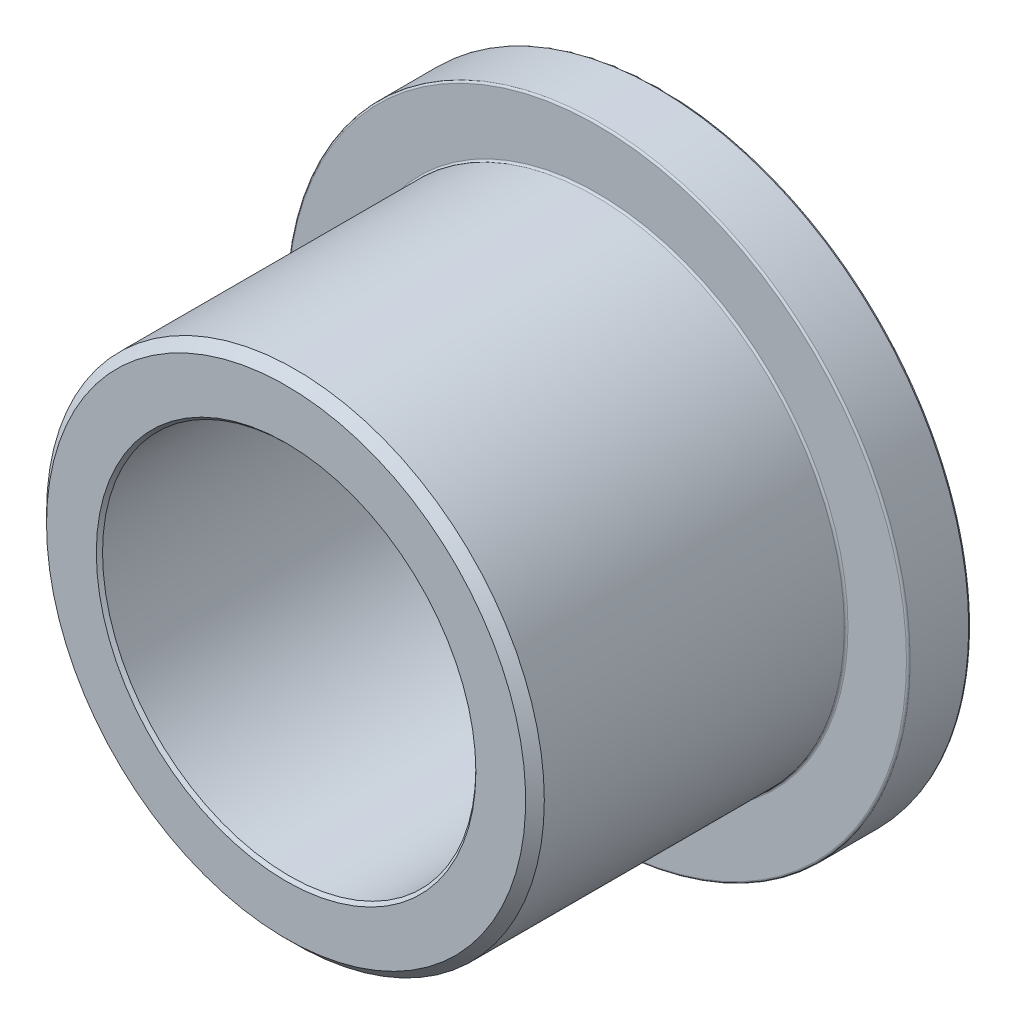
SolidWorks part; units mm, degrees
ref_plane "Front Plane" through (0, 0, 0) normal (0, 0, 1) x (1, 0, 0)
ref_plane "Top Plane" through (0, 0, 0) normal (0, 1, 0) x (1, 0, 0)
ref_plane "Right Plane" through (0, 0, 0) normal (1, 0, 0) x (0, 0, -1)
sketch "Sketch1" plane through (0, 0, 0) normal (0, 0, 1) x (1, 0, 0)
  circle A0 centre (0, 0) radius 4.7625 construction
  circle A1 centre (0, 0) radius 6.35 construction
  circle A2 centre (0, 0) radius 7.9375 construction
  point P5 (0, 7.9375)
  dimension "ID" = 9.525
  dimension "OD" = 12.7
  dimension "Flange OD" = 15.875
sketch "Sketch2" plane through (0, 0, 0) normal (1, 0, 0) x (0, 0, -1)
  line L0 (-4.7625, 0) -> (4.7625, 0) construction
  line L1 (-4.7625, 6.35) -> (-4.7625, -6.35) construction
  line L2 (0, 6.35) -> (0, -6.35) construction
  line L3 (4.7625, 7.9375) -> (4.7625, -7.9375) construction
  line L4 (0, 7.9375) -> (0, -7.9375) construction
  line L5 (4.7625, -7.9375) -> (3.175, -7.9375) construction
  dimension "Length" = 9.525
  dimension "Flange Thickness" = 1.5875
sketch "Sketch3" plane through (0, 0, 0) normal (1, 0, 0) x (0, 0, -1)
  line L0 (4.7625, -7.9375) -> (3.175, -7.9375)
  line L1 (3.175, -7.9375) -> (3.175, -6.35)
  line L2 (3.175, -6.35) -> (-4.7625, -6.35)
  line L3 (-4.7625, -6.35) -> (-4.7625, -4.7625)
  line L4 (-4.7625, 6.35) -> (-4.7625, -6.35) construction
  line L5 (-4.7625, -4.7625) -> (4.7625, -4.7625)
  line L6 (4.7625, 7.9375) -> (4.7625, -7.9375) construction
  line L7 (4.7625, -4.7625) -> (4.7625, -7.9375)
  line L9 (0, 4.7625) -> (0, -4.7625) construction
  point P15 (0, -4.7625)
revolve "Revolve1" add sketch "Sketch3" angle 360 about L0
chamfer "Chamfer1" distance 0.2381 angle 45 1 edges at (6.35, 0, 4.7625)
chamfer "Chamfer2" distance 0.0794 angle 45 2 edges at (4.7625, 0, -4.7625) (4.7625, 0, 4.7625)
fillet "Fillet1" radius 0.0476 3 edges at (7.9375, 0, -4.7625) (6.35, 0, -3.175) (7.9375, 0, -3.175)
equation "\"D1@Chamfer1\"=(\"OD@Sketch1\"-\"ID@Sketch1\")*0.075"
equation "\"D1@Chamfer2\"=(\"OD@Sketch1\"-\"ID@Sketch1\")*0.025"
equation "\"D1@Fillet1\"=(\"Flange OD@Sketch1\"-\"OD@Sketch1\")*0.015"
